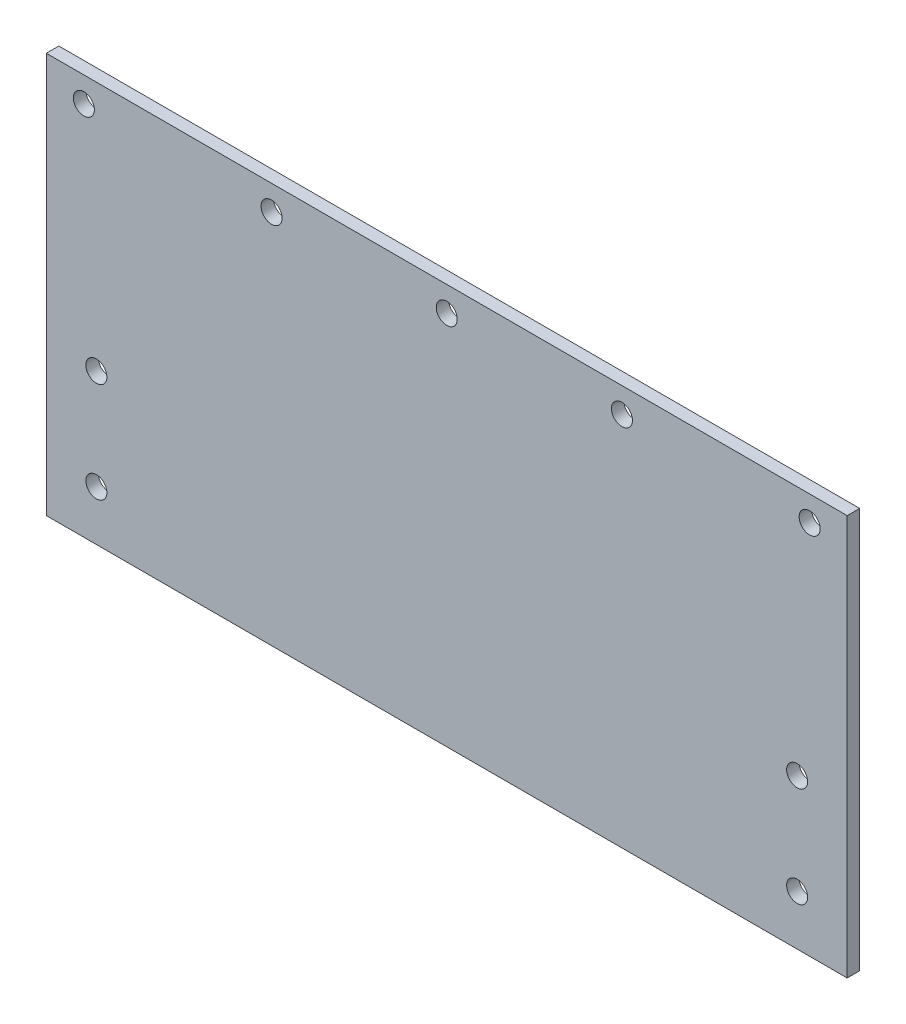
SolidWorks part; units mm, degrees
material "ABS PC"
ref_plane "Front Plane" through (0, 0, 0) normal (0, 0, 1) x (1, 0, 0)
ref_plane "Top Plane" through (0, 0, 0) normal (0, 1, 0) x (1, 0, 0)
ref_plane "Right Plane" through (0, 0, 0) normal (1, 0, 0) x (0, 0, -1)
sketch "Sketch1" plane through (0, 0, 0) normal (0, 0, 1) x (1, 0, 0)
  line L5 (160, -80) -> (-160, -80)
  line L6 (160, -80) -> (160, 80)
  line L7 (160, 80) -> (-160, 80)
  line L8 (-160, -80) -> (-160, 80)
  line L9 (160, -80) -> (-160, 80) construction
  line L10 (160, 80) -> (-160, -80) construction
  point P0 (0, 0)
  dimension "D1" = 320
  dimension "D2" = 160
extrude "Boss-Extrude1" add sketch "Sketch1" along normal blind 5 contours L7 L8 L5 L6
sketch "Sketch2" plane through (0, 0, 5) normal (0, 0, 1) x (1, 0, 0)
  line L0 (0, -55) -> (0, 55) construction
  line L1 (-160, -80) -> (-160, 80) construction
  line L2 (160, 80) -> (-160, 80) construction
  line L3 (160, -80) -> (-160, -80) construction
  point P0 (-145, 70)
  point P1 (-70, 70)
  point P2 (0, 70)
  point P5 (70, 70)
  point P6 (145, 70)
  point P9 (-140, -60)
  point P15 (-140, -20)
  point P18 (140, -20)
  point P19 (140, -60)
  dimension "D1" = 15
  dimension "D2" = 75
  dimension "D3" = 10
  dimension "D4" = 20
  dimension "D5" = 40
  dimension "D6" = 20
hole_wizard "M8 Clearance Hole1" positions "Sketch3" profile "Sketch4" hole size "M8" standard "GB" end condition through all
sketch "Sketch3" plane through (0, 0, 5) normal (0, 0, 1) x (1, 0, 0)
  point P0 (-145, 70)
  point P3 (-70, 70)
  point P6 (0, 70)
  point P9 (70, 70)
  point P12 (145, 70)
  point P15 (-140, -20)
  point P18 (-140, -60)
  point P21 (140, -20)
  point P24 (140, -60)
sketch "Sketch4" plane through (-145, 70, 5) normal (1, 0, 0) x (0, -1, 0)
  line L0 (0, 0) -> (0, 5)
  line L1 (0, 5) -> (4.2, 5)
  line L2 (4.2, 5) -> (4.2, 0)
  line L5 (4.2, 0) -> (0, 0)
  line L11 (0, -6.35) -> (0, 107.95) construction
  dimension "Thru Hole Dia." = 8.4
  dimension "Thru Hole Depth" = 5
